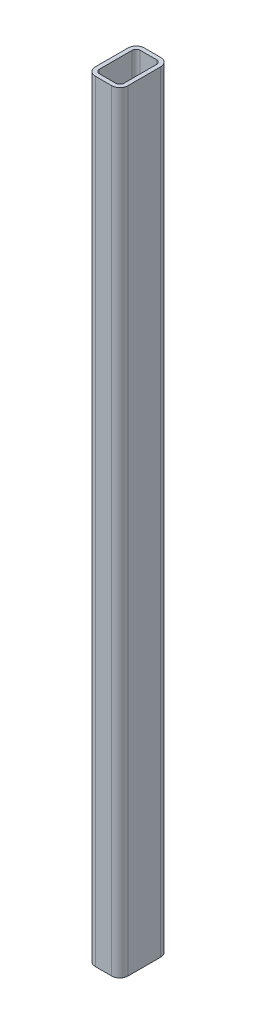
SolidWorks part; units mm, degrees
material "Fundición gris"
ref_plane "Alzado" through (0, 0, 0) normal (0, 0, 1) x (1, 0, 0)
ref_plane "Planta" through (0, 0, 0) normal (0, 1, 0) x (1, 0, 0)
ref_plane "Vista lateral" through (0, 0, 0) normal (1, 0, 0) x (0, 0, -1)
sketch "Croquis1" plane through (0, 0, 0) normal (0, 0, 1) x (1, 0, 0)
  line L0 (0, 0) -> (0, 1200)
  dimension "D1" = 1200
other "Tubo rectangular 3 X 2 X 0.25(1)"
ref_plane "Plano1" through (0, 0, 0) normal (0, 1, 0) x (-1, 0, 0)
sketch "Sketch1" plane through (0, 0, 0) normal (0, 1, 0) x (-1, 0, 0)
  line L0 (-12.7, -31.75) -> (12.7, -31.75)
  line L1 (-19.05, -25.4) -> (-19.05, 25.4)
  line L2 (12.7, 31.75) -> (-12.7, 31.75)
  line L3 (19.05, 25.4) -> (19.05, -25.4)
  line L4 (-12.7, -38.1) -> (12.7, -38.1)
  line L5 (-25.4, -25.4) -> (-25.4, 25.4)
  line L6 (12.7, 38.1) -> (-12.7, 38.1)
  line L7 (25.4, 25.4) -> (25.4, -25.4)
  line L8 (0, 0) -> (25.4, 0) construction
  line L9 (0, 0) -> (0, 38.1) construction
  arc A0 (25.4, 25.4) -> (12.7, 38.1) centre (12.7, 25.4) ccw
  arc A1 (12.7, -38.1) -> (25.4, -25.4) centre (12.7, -25.4) ccw
  arc A2 (-25.4, -25.4) -> (-12.7, -38.1) centre (-12.7, -25.4) ccw
  arc A3 (-12.7, 38.1) -> (-25.4, 25.4) centre (-12.7, 25.4) ccw
  arc A4 (-12.7, 31.75) -> (-19.05, 25.4) centre (-12.7, 25.4) ccw
  arc A5 (19.05, 25.4) -> (12.7, 31.75) centre (12.7, 25.4) ccw
  arc A6 (12.7, -31.75) -> (19.05, -25.4) centre (12.7, -25.4) ccw
  arc A7 (-19.05, -25.4) -> (-12.7, -31.75) centre (-12.7, -25.4) ccw
  point P3 (0, -38.1)
  point P4 (-25.4, 0)
  point P5 (0, 0)
  point P6 (25.4, -38.1)
  point P7 (-25.4, -38.1)
  point P8 (-25.4, 38.1)
  point P33 (0, 0)
  point P35 (25.4, 38.1)
  point P36 (25.4, 0)
  point P37 (0, 38.1)
  dimension "D1" = 12.7
  dimension "Thickness" = 6.35
  dimension "V_leg" = 76.2
  dimension "H_leg" = 50.8
